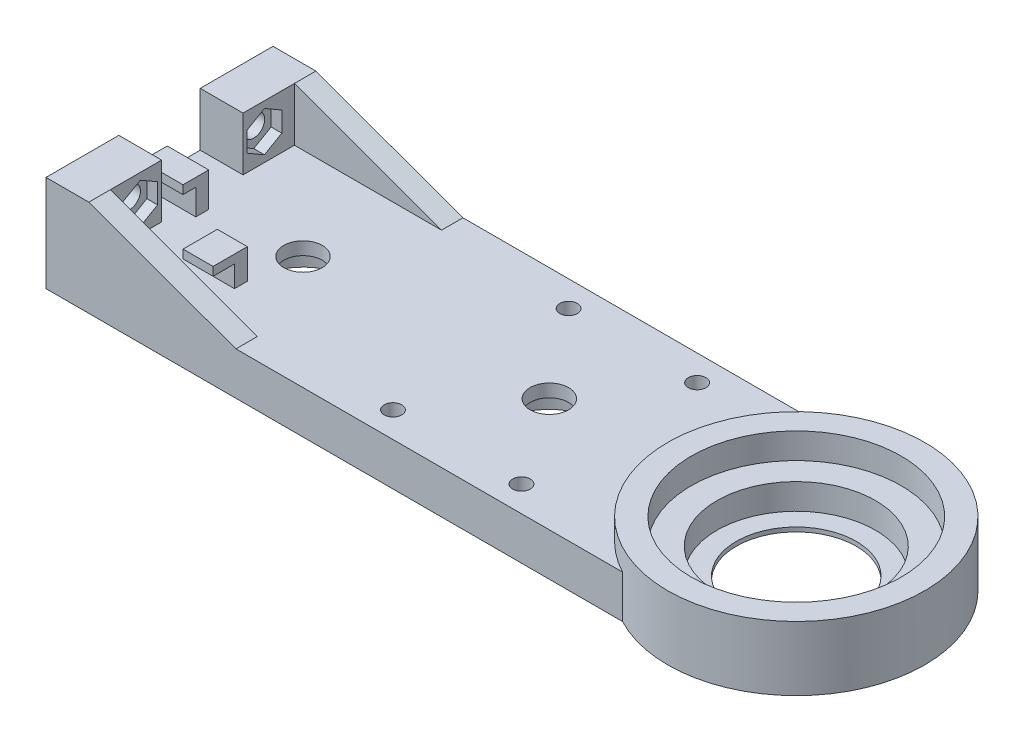
SolidWorks part; units mm, degrees
ref_plane "Front Plane" through (0, 0, 0) normal (0, 0, 1) x (1, 0, 0)
ref_plane "Top Plane" through (0, 0, 0) normal (0, 1, 0) x (1, 0, 0)
ref_plane "Right Plane" through (0, 0, 0) normal (1, 0, 0) x (0, 0, -1)
sketch "Sketch2" plane through (0, 0, 0) normal (0, 1, 0) x (1, 0, 0)
  line L1 (-74, 26.5) -> (74.6515, 26.5)
  line L2 (-74, 26.5) -> (-74, -26.5)
  line L3 (-74, -26.5) -> (74.6515, -26.5)
  arc A1 (74.6515, -26.5) -> (74.6515, 26.5) centre (74.6515, 0) ccw
  point P0 (0, 0)
  dimension "D2" = 53
  dimension "D1" = 53
  dimension "D3" = 148.6515
extrude "Boss-Extrude1" add sketch "Sketch2" along normal blind 10
sketch "Sketch3" plane through (0, 10, 0) normal (0, 1, 0) x (1, 0, 0)
  line L0 (-74, 26.5) -> (-74, -26.5) construction
  line L1 (-74, -9.5) -> (-64, -9.5)
  line L2 (-74, -9.5) -> (-74, -26.5)
  line L3 (-74, -26.5) -> (-64, -26.5)
  line L4 (-64, -9.5) -> (-64, -26.5)
  line L5 (-74, -26.5) -> (74.6515, -26.5) construction
  line L7 (-74, 26.5) -> (-64, 26.5)
  line L8 (-74, 26.5) -> (-74, 9.5)
  line L9 (-74, 9.5) -> (-64, 9.5)
  line L10 (-64, 26.5) -> (-64, 9.5)
  dimension "D1" = 10
  dimension "D2" = 17
  dimension "D3" = 10
  dimension "D4" = 17
extrude "Boss-Extrude2" add sketch "Sketch3" along normal blind 12.5
sketch "Sketch4" plane through (0, 0, 26.5) normal (0, 0, 1) x (1, 0, 0)
  line L0 (-64, 22.5) -> (-29.6565, 10)
  line L1 (-64, 10) -> (74.6515, 10) construction
  dimension "D1" = 20
rib "Rib1" sketch "Sketch4" sketch "Sketch4" thickness 5 extrusion direction parallel to sketch draft on no parameters "D1"=5
mirror "Mirror1" about plane through (0, 0, 0) normal (0, 0, 1) of "Rib1"
sketch "Sketch6" plane through (-64, 0, 0) normal (1, 0, 0) x (0, 0, -1)
  line L6 (-21.5, 10) -> (-21.5, 22.5) construction
  circle A0 centre (-14.5, 16.25) radius 2.55
  dimension "D1" = 5.1
  dimension "D2" = 7
extrude "Cut-Extrude1" cut sketch "Sketch6" against normal up to next
sketch "Sketch7" plane through (-64, 0, 0) normal (1, 0, 0) x (0, 0, -1)
  line L0 (-21.5, 10) -> (-21.5, 22.5) construction
  line L13 (-10.45, 13.9117) -> (-10.45, 18.5883)
  line L14 (-10.45, 18.5883) -> (-14.5, 20.9265)
  line L15 (-14.5, 20.9265) -> (-18.55, 18.5883)
  line L16 (-18.55, 18.5883) -> (-18.55, 13.9117)
  line L17 (-18.55, 13.9117) -> (-14.5, 11.5735)
  line L18 (-14.5, 11.5735) -> (-10.45, 13.9117)
  circle A0 centre (-14.5, 16.25) radius 4.05 construction
  dimension "D1" = 8.1
extrude "Cut-Extrude2" cut sketch "Sketch7" against normal blind 2.5
mirror "Mirror2" about plane through (0, 0, 0) normal (0, 0, 1) of "Cut-Extrude2", "Cut-Extrude1"
sketch "Sketch11" plane through (0, 10, 0) normal (0, 1, 0) x (1, 0, 0)
  circle A0 centre (74.6515, 0) radius 30
  arc A1 (74.6515, -26.5) -> (74.6515, 26.5) centre (74.6515, 0) ccw construction
  dimension "D1" = 60
extrude "Boss-Extrude4" add sketch "Sketch11" along normal blind 5 and the other way blind 10
sketch "Sketch8" plane through (0, 10, 0) normal (0, 1, 0) x (1, 0, 0)
  circle A0 centre (74.6515, 0) radius 14
  circle A2 centre (74.6515, 0) radius 30 construction
  dimension "D1" = 28
extrude "Cut-Extrude3" cut sketch "Sketch8" against normal up to next
sketch "Sketch9" plane through (0, 10, 0) normal (0, 1, 0) x (1, 0, 0)
  circle A0 centre (74.6515, 0) radius 18.5
  dimension "D1" = 37
extrude "Cut-Extrude4" cut sketch "Sketch9" against normal blind 7 and the other way blind 6
sketch "Sketch12" plane through (0, 15, 0) normal (0, 1, 0) x (1, 0, 0)
  circle A0 centre (74.6515, 0) radius 24.5
  dimension "D1" = 49
extrude "Cut-Extrude6" cut sketch "Sketch12" against normal blind 6
sketch "Sketch13" plane through (0, 10, 0) normal (0, 1, 0) x (1, 0, 0)
  line L0 (1, -20.5) -> (31, -20.5) construction
  line L1 (-29.6565, -26.5) -> (60.5892, -26.5) construction
  line L2 (-74, 9.5) -> (-74, -9.5) construction
  circle A0 centre (1, -20.5) radius 2.05
  circle A1 centre (31, -20.5) radius 2.05
  dimension "D3" = 4.1
  dimension "D4" = 4.1
  dimension "D1" = 30
  dimension "D2" = 6
  dimension "D5" = 75
extrude "Cut-Extrude7" cut sketch "Sketch13" against normal through all
sketch "Sketch15" plane through (0, 0, 0) normal (0, -1, 0) x (1, 0, 0)
  circle A0 centre (74.6515, 0) radius 24.5
  dimension "D1" = 49
extrude "Cut-Extrude9" cut sketch "Sketch15" against normal blind 2
sketch "Sketch17" plane through (0, 0, 0) normal (0, -1, 0) x (1, 0, 0)
  circle A0 centre (-40.5, 0) radius 11.1
  dimension "D2" = 22.2
  dimension "D1" = 40.5
extrude "Cut-Extrude11" cut sketch "Sketch17" against normal blind 7
sketch "Sketch18" plane through (0, 7, 0) normal (0, -1, 0) x (1, 0, 0)
  circle A0 centre (-40.5, 0) radius 4.5
  dimension "D1" = 9
extrude "Cut-Extrude12" cut sketch "Sketch18" against normal up to next
sketch "Sketch19" plane through (0, 0, 0) normal (0, -1, 0) x (1, 0, 0)
  circle A0 centre (17, 0) radius 11.1
  dimension "D1" = 22.2
  dimension "D2" = 17
extrude "Cut-Extrude13" cut sketch "Sketch19" against normal blind 7
sketch "Sketch20" plane through (0, 7, 0) normal (0, -1, 0) x (1, 0, 0)
  circle A0 centre (17, 0) radius 4.5
  dimension "D1" = 9
extrude "Cut-Extrude14" cut sketch "Sketch20" against normal up to next
mirror "Mirror3" about plane through (0, 0, 0) normal (0, 0, 1) of "Cut-Extrude7"
sketch "Sketch21" plane through (0, 10, 0) normal (0, 1, 0) x (1, 0, 0)
  line L4 (-49, -14.5) -> (-42, -14.5)
  line L5 (-42, -14.5) -> (-42, -11.5)
  line L6 (-64, -21.5) -> (-29.6565, -21.5) construction
  line L8 (-42, -11.5) -> (-49, -11.5)
  line L9 (-49, -11.5) -> (-49, -14.5)
  line L10 (-64, -21.5) -> (-64, -9.5) construction
  dimension "D1" = 3
  dimension "D2" = 15
  dimension "D3" = 7
  dimension "D4" = 7
extrude "Boss-Extrude5" add sketch "Sketch21" along normal blind 7
sketch "Sketch22" plane through (0, 0, 14.5) normal (0, 0, 1) x (1, 0, 0)
  line L0 (-42, 17) -> (-42, 10) construction
  line L1 (-49, 17) -> (-42, 17)
  line L2 (-49, 17) -> (-49, 15)
  line L3 (-49, 15) -> (-42, 15)
  line L4 (-42, 17) -> (-42, 15)
  dimension "D1" = 2
extrude "Boss-Extrude6" add sketch "Sketch22" along normal blind 5
sketch "Sketch23" plane through (0, 10, 0) normal (0, 1, 0) x (1, 0, 0)
  line L0 (-64, -9.5) -> (-74, -9.5) construction
  line L1 (-70.6954, -1.5) -> (-61.0201, -1.5)
  line L2 (-70.6954, -1.5) -> (-70.6954, -4.5)
  line L3 (-70.6954, -4.5) -> (-61.0201, -4.5)
  line L4 (-61.0201, -1.5) -> (-61.0201, -4.5)
  dimension "D1" = 3
  dimension "D2" = 5
extrude "Boss-Extrude7" add sketch "Sketch23" along normal blind 8
sketch "Sketch24" plane through (0, 0, 4.5) normal (0, 0, 1) x (1, 0, 0)
  line L0 (-61.0201, 18) -> (-61.0201, 10) construction
  line L1 (-70.6954, 18) -> (-61.0201, 18)
  line L2 (-70.6954, 18) -> (-70.6954, 16)
  line L3 (-70.6954, 16) -> (-61.0201, 16)
  line L4 (-61.0201, 18) -> (-61.0201, 16)
  dimension "D1" = 2
extrude "Boss-Extrude8" add sketch "Sketch24" along normal blind 3
